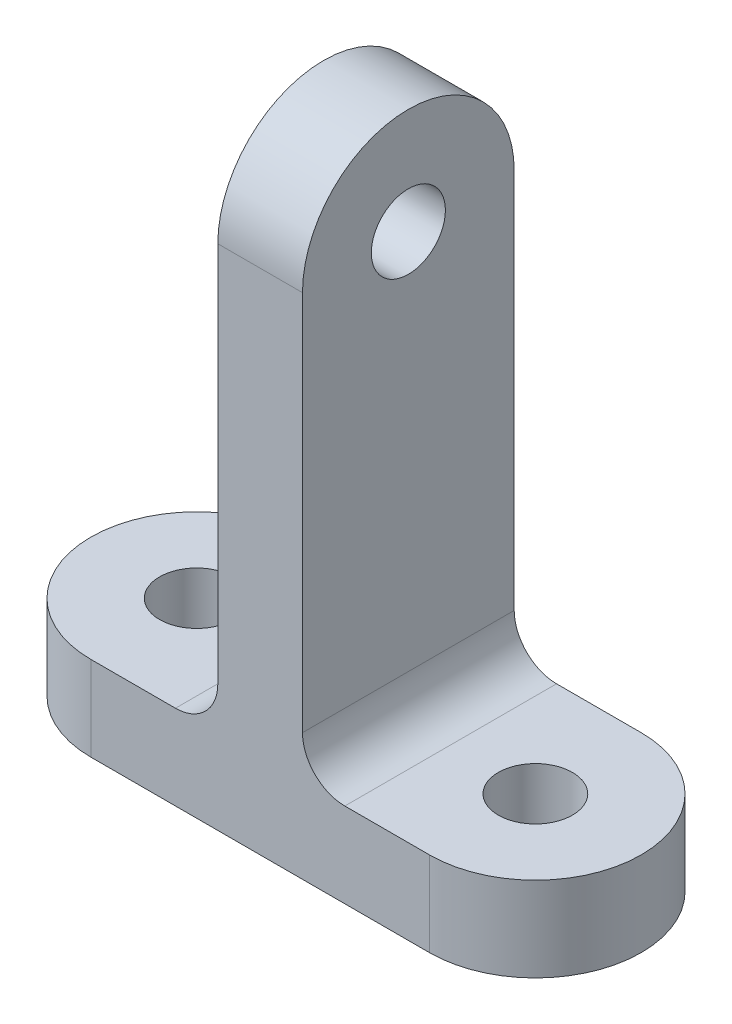
SolidWorks part; units mm, degrees
ref_plane "Front Plane" through (0, 0, 0) normal (0, 0, 1) x (1, 0, 0)
ref_plane "Top Plane" through (0, 0, 0) normal (0, 1, 0) x (1, 0, 0)
ref_plane "Right Plane" through (0, 0, 0) normal (1, 0, 0) x (0, 0, -1)
sketch "Sketch1" plane through (0, 0, 0) normal (0, 1, 0) x (1, 0, 0)
  line L0 (-8, 5) -> (8, 5)
  line L1 (8, -5) -> (-8, -5)
  circle A0 centre (-8, 0) radius 1.75
  circle A1 centre (8, 0) radius 1.75
  circle A2 centre (-8, 0) radius 5
  circle A3 centre (8, 0) radius 5
  dimension "D1" = 3.5
  dimension "D2" = 3.5
  dimension "D5" = 10
  dimension "D6" = 10
  dimension "D3" = 8
  dimension "D4" = 8
extrude "Boss-Extrude1" add sketch "Sketch1" along normal blind 4 contours A2 A0 | A3 L0 A2 L1 | A3 A1
sketch "Sketch2" plane through (0, 4, 0) normal (0, 1, 0) x (1, 0, 0)
  line L0 (8, -5) -> (-8, -5) construction
  line L1 (2, 5) -> (-2, 5)
  line L2 (2, 5) -> (2, -5)
  line L3 (2, -5) -> (-2, -5)
  line L4 (-2, 5) -> (-2, -5)
  line L5 (2, 5) -> (-2, -5) construction
  line L6 (2, -5) -> (-2, 5) construction
  point P0 (0, 0)
  dimension "D1" = 4
extrude "Boss-Extrude2" add sketch "Sketch2" along normal blind 25
sketch "Sketch3" plane through (2, 0, 0) normal (1, 0, 0) x (0, 0, -1)
  line L0 (-5, 29) -> (5, 29) construction
  line L5 (-5, 4) -> (5, 4)
  line L6 (5, 4) -> (5, 29)
  line L7 (5, 29) -> (-5, 29)
  line L8 (-5, 29) -> (-5, 4)
  line L9 (-5, 4) -> (5, 4)
  line L10 (5, 4) -> (5, 29)
  line L11 (5, 29) -> (-5, 29)
  line L12 (-5, 29) -> (-5, 4)
  circle A0 centre (0, 24) radius 1.75
  circle A1 centre (0, 24) radius 5
  line M9 (5, 29) -> (-5, 29)
  line M10 (-5, 29) -> (-5, 4)
  dimension "D2" = 3.5
  dimension "D1" = 5
  dimension "D3" = 0
extrude "Cut-Extrude1" cut sketch "Sketch3" against normal up to surface (4 mm away) contours A1 L11 M10 | A1 L10 M9 | A0 up to face at (-2, 16.5, 0)
fillet "Fillet1" radius 2 1 edges at (2, 4, 0)
fillet "Fillet2" radius 2 1 edges at (-2, 4, 0)
